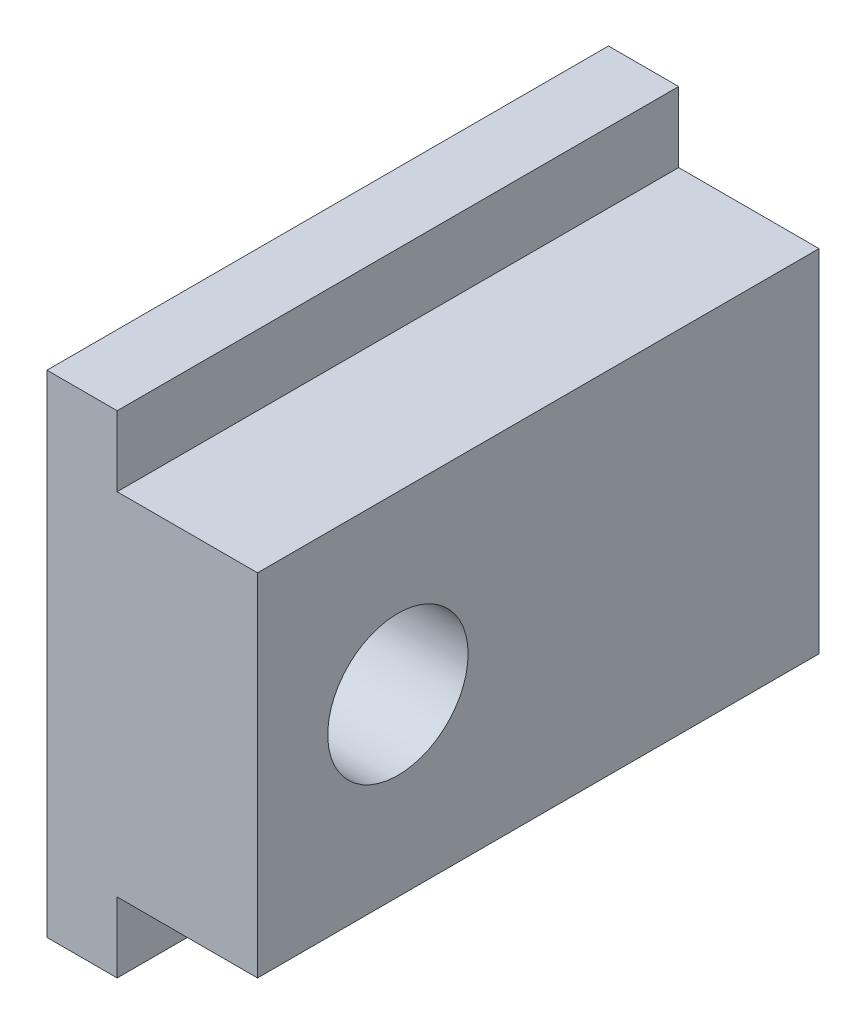
SolidWorks part; units mm, degrees
material "Magnesium Alloy"
ref_plane "Front Plane" through (0, 0, 0) normal (0, 0, 1) x (1, 0, 0)
ref_plane "Top Plane" through (0, 0, 0) normal (0, 1, 0) x (1, 0, 0)
ref_plane "Right Plane" through (0, 0, 0) normal (1, 0, 0) x (0, 0, -1)
sketch "Sketch1" plane through (0, 0, 0) normal (0, 0, 1) x (1, 0, 0)
  line L0 (0, 0) -> (3.175, 0)
  line L1 (3.175, 0) -> (3.175, 3.175)
  line L2 (3.175, 3.175) -> (9.525, 3.175)
  line L3 (9.525, 3.175) -> (9.525, 19.05)
  line L4 (9.525, 19.05) -> (3.175, 19.05)
  line L5 (3.175, 19.05) -> (3.175, 22.225)
  line L6 (3.175, 22.225) -> (0, 22.225)
  line L7 (0, 22.225) -> (0, 0)
  dimension "D1" = 22.225
  dimension "D2" = 15.875
  dimension "D3" = 3.175
  dimension "D4" = 6.35
extrude "Boss-Extrude1" add sketch "Sketch1" along normal blind 25.4
sketch "Sketch3" plane through (9.525, 0, 0) normal (1, 0, 0) x (0, 0, -1)
  line L0 (-25.4, 3.175) -> (-25.4, 19.05) construction
  line L1 (-25.4, 19.05) -> (0, 19.05) construction
  circle A0 centre (-19.05, 11.1125) radius 3.175
  dimension "D1" = 6.35
  dimension "D2" = 6.35
  dimension "D3" = 7.9375
extrude "Cut-Extrude1" cut sketch "Sketch3" against normal through all
hole_wizard "1/4 (0.25) Diameter Hole1" positions "Sketch4" profile "Sketch5" hole size "1/4" standard "ANSI Inch"
sketch "Sketch4" plane through (0, 0, 0) normal (0, 0, -1) x (-1, 0, 0)
  line L0 (-9.525, 3.175) -> (-9.525, 19.05) construction
  line L1 (-3.175, 3.175) -> (-9.525, 3.175) construction
  point P0 (-4.7625, 11.1125)
  dimension "D1" = 4.7625
  dimension "D2" = 7.9375
sketch "Sketch5" plane through (4.7625, 11.1125, 0) normal (1, 0, 0) x (0, 1, 0)
  line L0 (0, 0) -> (0, 14.6077)
  line L1 (0, 14.6077) -> (3.175, 12.7)
  line L2 (3.175, 12.7) -> (3.175, 0)
  line L5 (3.175, 0) -> (0, 0)
  line L10 (0, 14.6077) -> (-3.175, 12.7) construction
  line L11 (0, -6.35) -> (0, 107.95) construction
  dimension "Hole Dia." = 6.35
  dimension "Hole Depth" = 12.7
  dimension "Drill Angle" = 118
